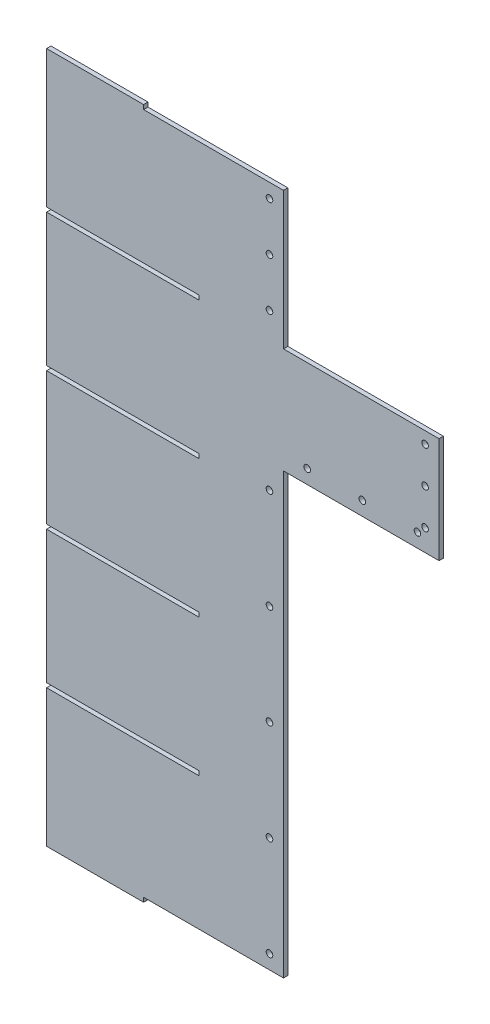
SolidWorks part; units mm, degrees
material "6061-T6 (SS)"
ref_plane "X-Y Datum" through (0, 0, 0) normal (0, 0, 1) x (1, 0, 0)
ref_plane "X-Z Datum" through (0, 0, 0) normal (0, 1, 0) x (1, 0, 0)
ref_plane "Y-Z Datum" through (0, 0, 0) normal (1, 0, 0) x (0, 0, -1)
sketch "Sketch1" plane through (0, 0, 0) normal (0, 0, 1) x (1, 0, 0)
  line L1 (129.0131, 254.2454) -> (-18.6854, 254.2454)
  line L3 (129.0131, -241.3467) -> (-18.6854, -241.3467)
  line L4 (-18.6854, 254.2454) -> (-18.6854, 157.667)
  line L24 (129.0131, 254.2454) -> (129.0131, -241.3467)
  line L25 (92.0885, 157.667) -> (-18.6854, 157.667)
  line L27 (92.0885, 154.492) -> (-18.6854, 154.492)
  line L29 (92.0885, 57.9136) -> (-18.6854, 57.9136)
  line L31 (92.0885, 54.7386) -> (-18.6854, 54.7386)
  line L33 (92.0885, -41.8399) -> (-18.6854, -41.8399)
  line L35 (92.0885, -45.0149) -> (-18.6854, -45.0149)
  line L37 (92.0885, -141.5933) -> (-18.6854, -141.5933)
  line L39 (92.0885, -144.7683) -> (-18.6854, -144.7683)
  line L41 (92.0885, -141.5933) -> (92.0885, -144.7683)
  line L42 (92.0885, -41.8399) -> (92.0885, -45.0149)
  line L43 (92.0885, 57.9136) -> (92.0885, 54.7386)
  line L44 (-18.6854, -144.7683) -> (-18.6854, -241.3467)
  line L45 (-18.6854, -45.0149) -> (-18.6854, -141.5933)
  line L46 (-18.6854, 54.7386) -> (-18.6854, -41.8399)
  line L47 (-18.6854, 154.492) -> (-18.6854, 57.9136)
  line L48 (92.0885, 157.667) -> (92.0885, 154.492)
extrude "Boss-Extrude2" add sketch "Sketch1" along normal blind 3.175
sketch "Sketch4" plane through (0, 0, 3.175) normal (0, 0, 1) x (1, 0, 0)
  line L0 (129.0131, 254.2454) -> (153.4072, 240.1614) construction
  line L2 (129.0131, 254.2454) -> (129.0131, -241.3467)
  line L4 (153.4072, 240.1614) -> (153.4072, -227.2627)
  line L6 (153.4072, -227.2627) -> (153.4072, -241.3467)
  line L7 (153.4072, -241.3467) -> (129.0131, -241.3467)
  line L8 (129.0131, 254.2454) -> (153.4072, 254.2454)
  line L9 (153.4072, 254.2454) -> (153.4072, 240.1614)
extrude "Boss-Extrude3" add sketch "Sketch4" against normal through all
sketch "Sketch7" plane through (0, 0, 3.175) normal (0, 0, 1) x (1, 0, 0)
  line L0 (51.8072, -241.3467) -> (-18.6854, -241.3467)
  line L1 (51.8072, -244.5217) -> (51.8072, -241.3467)
  line L2 (153.4072, -244.5217) -> (51.8072, -244.5217)
  line L3 (153.4072, -244.5217) -> (153.4072, -257.2217)
  line L4 (153.4072, -257.2217) -> (30.4963, -257.2217)
  line L5 (30.4963, -257.2217) -> (6.7146, -273.4777)
  line L6 (-18.6854, -273.4777) -> (6.7146, -273.4777)
  line L7 (-18.6854, -241.3467) -> (-18.6854, -273.4777)
  point P0 (-51.634, -260.9767)
  point P9 (-18.6854, -241.3467)
extrude "Boss-Extrude6" [suppressed] add sketch "Sketch7" against normal through all
sketch "Sketch8" [suppressed] plane through (0, 0, 3.175) normal (0, 0, 1) x (1, 0, 0)
  line L1 (153.4072, -257.2217) -> (221.7231, -257.2217)
  line L2 (153.4072, -257.2217) -> (153.4072, -244.5217)
  line L3 (153.4072, -244.5217) -> (221.7231, -244.5217)
  line L4 (221.7231, -257.2217) -> (221.7231, -244.5217)
  line L5 (153.4072, -241.3467) -> (221.7231, -241.3467)
  line L6 (153.4072, -241.3467) -> (153.4072, -144.7683)
  line L7 (153.4072, -144.7683) -> (221.7231, -144.7683)
  line L8 (221.7231, -241.3467) -> (221.7231, -144.7683)
  dimension "D1" = 68.3158
extrude "Boss-Extrude7" [suppressed] add sketch "Sketch8" against normal through all
sketch "Sketch11" plane through (0, 0, 3.175) normal (0, 0, 1) x (1, 0, 0)
  line L1 (153.4072, 154.492) -> (266.4372, 154.492)
  line L2 (153.4072, -241.3467) -> (153.4072, 254.2454) construction
  line L3 (266.4372, 154.492) -> (266.4372, 77.7256)
  line L4 (266.4372, 77.7256) -> (153.4072, 77.7256)
  line L5 (153.4072, 77.7256) -> (153.4072, 154.492)
extrude "Boss-Extrude8" add sketch "Sketch11" against normal through all
sketch "Sketch12" plane through (0, 0, 0) normal (0, 0, -1) x (-1, 0, 0)
  line L1 (18.6854, 254.2454) -> (-51.8072, 254.2454)
  line L2 (18.6854, 254.2454) -> (18.6854, 257.4204)
  line L3 (18.6854, 257.4204) -> (-51.8072, 257.4204)
  line L4 (-51.8072, 254.2454) -> (-51.8072, 257.4204)
  line L5 (18.6854, -241.3467) -> (-51.8072, -241.3467)
  line L6 (18.6854, -241.3467) -> (18.6854, -244.5217)
  line L7 (18.6854, -244.5217) -> (-51.8072, -244.5217)
  line L8 (-51.8072, -241.3467) -> (-51.8072, -244.5217)
extrude "Boss-Extrude9" add sketch "Sketch12" against normal through all
sketch "Sketch14" plane through (0, 0, 3.175) normal (0, 0, 1) x (1, 0, 0)
  line L0 (-18.6854, -244.5217) -> (269.694, -244.5217)
  line L1 (-18.6854, -244.5217) -> (-18.6854, 277.9004)
  line L2 (-18.6854, 277.9004) -> (269.694, 277.9004)
  line L3 (269.694, -244.5217) -> (269.694, 277.9004)
  point P0 (143.2472, -231.1146)
  point P1 (143.2472, -158.2226)
  point P2 (143.2472, -85.3305)
  point P3 (143.2472, -12.4385)
  point P4 (143.2472, 60.4536)
  point P5 (170.6792, 87.8856)
  point P6 (210.7117, 87.8856)
  point P7 (250.7441, 87.8856)
  point P8 (256.2772, 93.4187)
  point P9 (256.2772, 119.6462)
  point P10 (256.2772, 145.8738)
  point P11 (143.2472, 173.5725)
  point P12 (143.2472, 208.7929)
  point P13 (143.2472, 244.0133)
hole_wizard "M4 Clearance Hole1" positions "Sketch15" profile "Sketch16" hole size "M4" standard "ANSI Metric" end condition through all
sketch "Sketch15" plane through (0, 0, 3.175) normal (0, 0, 1) x (1, 0, 0)
  point P0 (143.2472, -231.1146)
  point P3 (143.2472, -158.2226)
  point P6 (143.2472, -85.3305)
  point P9 (143.2472, -12.4385)
  point P12 (143.2472, 60.4536)
  point P15 (170.6792, 87.8856)
  point P18 (210.7117, 87.8856)
  point P21 (250.7441, 87.8856)
  point P24 (256.2772, 93.4187)
  point P27 (256.2772, 119.6462)
  point P30 (256.2772, 145.8738)
  point P33 (143.2472, 173.5725)
  point P36 (143.2472, 208.7929)
  point P39 (143.2472, 244.0133)
sketch "Sketch16" plane through (143.2472, -231.1146, 3.175) normal (1, 0, 0) x (0, -1, 0)
  line L0 (0, 0) -> (0, 3.175)
  line L1 (0, 3.175) -> (2.4, 3.175)
  line L2 (2.4, 3.175) -> (2.4, 0)
  line L5 (2.4, 0) -> (0, 0)
  line L11 (0, -6.35) -> (0, 107.95) construction
  dimension "Thru Hole Dia." = 4.8
  dimension "Thru Hole Depth" = 3.175
